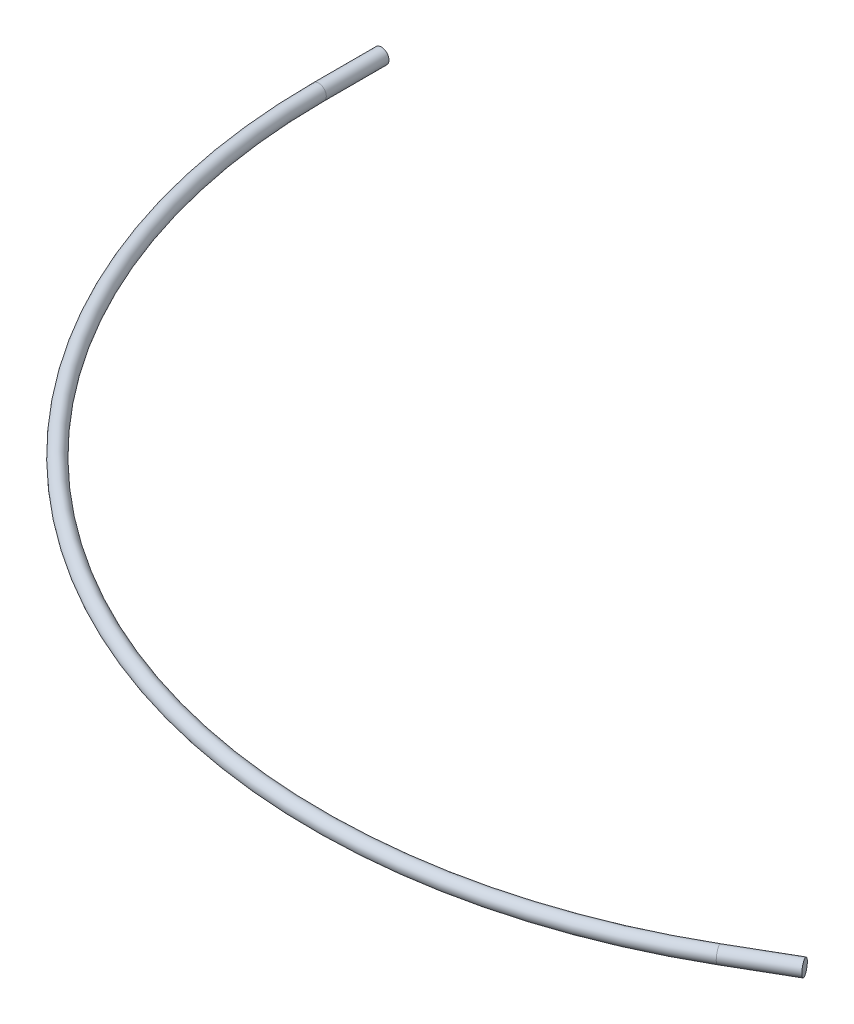
SolidWorks part; units mm, degrees
ref_plane "Front Plane" through (0, 0, 0) normal (0, 0, 1) x (1, 0, 0)
ref_plane "Top Plane" through (0, 0, 0) normal (0, 1, 0) x (1, 0, 0)
ref_plane "Right Plane" through (0, 0, 0) normal (1, 0, 0) x (0, 0, -1)
sketch "Sketch2" plane through (0, 0, 0) normal (0, 0, 1) x (1, 0, 0)
  line L0 (0, 0) -> (0, 44.3744) construction
sketch "Sketch3" plane through (0, 0, 0) normal (0, 0, 1) x (1, 0, 0)
  line L0 (0, 0) -> (-201.5, 0) construction
  circle A0 centre (-201.5, 0) radius 2.4
revolve "Revolve1" add sketch "Sketch3" angle 120 about L0
sketch "Sketch4" plane through (0, 0, 0) normal (0.866, 0, -0.5) x (-0.5, 0, -0.866)
  circle A0 centre (-201.5, 0) radius 2.4
extrude "Boss-Extrude1" add sketch "Sketch4" along normal blind 20
sketch "Sketch5" plane through (0, 0, 0) normal (0, 0, -1) x (-1, 0, 0)
  circle A0 centre (201.5, 0) radius 2.4
extrude "Boss-Extrude2" add sketch "Sketch5" along normal blind 20
